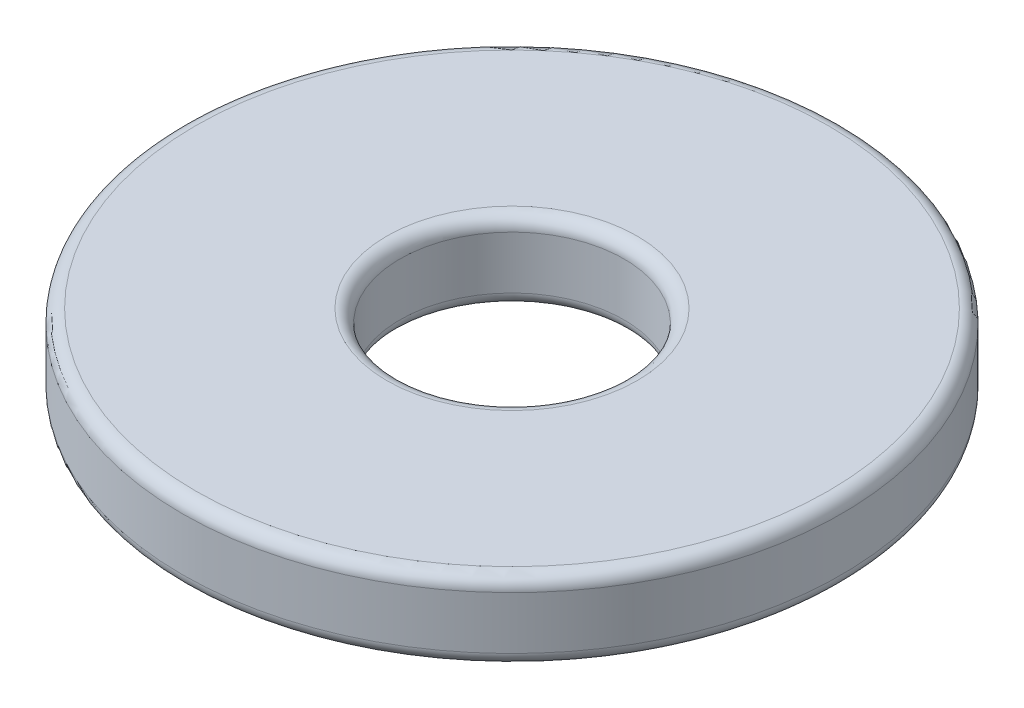
SolidWorks part; units mm, degrees
ref_plane "Alzado" through (0, 0, 0) normal (0, 0, 1) x (1, 0, 0)
ref_plane "Planta" through (0, 0, 0) normal (0, 1, 0) x (1, 0, 0)
ref_plane "Vista lateral" through (0, 0, 0) normal (1, 0, 0) x (0, 0, -1)
sketch "Croquis1" plane through (0, 0, 0) normal (0, 1, 0) x (1, 0, 0)
  circle A0 centre (0, 0) radius 12.5
  circle A1 centre (0, 0) radius 4.25
  dimension "D1" = 8.5
  dimension "D2" = 25
extrude "Saliente-Extruir1" add sketch "Croquis1" along normal blind 3
fillet "Redondeo1" radius 0.5 4 edges at (0, 0, 12.5) (0, 3, 12.5) (0, 0, 4.25) (0, 3, 4.25)
